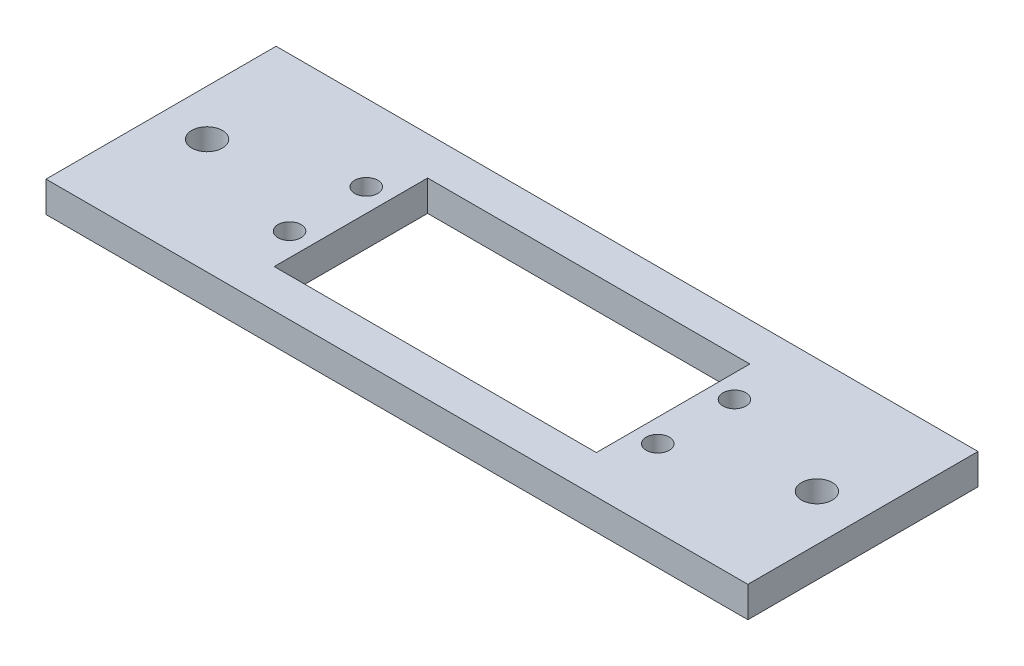
SolidWorks part; units mm, degrees
material "Balsa"
ref_plane "Front Plane" through (0, 0, 0) normal (0, 0, 1) x (1, 0, 0)
ref_plane "Top Plane" through (0, 0, 0) normal (0, 1, 0) x (1, 0, 0)
ref_plane "Right Plane" through (0, 0, 0) normal (1, 0, 0) x (0, 0, -1)
sketch "Sketch1" plane through (0, 0, 0) normal (0, 1, 0) x (1, 0, 0)
  line L0 (-21, 10) -> (-27.75, 10) construction
  line L1 (-21, -10) -> (21, -10)
  line L2 (-21, -10) -> (-21, 10)
  line L3 (-21, 10) -> (21, 10)
  line L4 (21, -10) -> (21, 10)
  line L5 (-21, -10) -> (21, 10) construction
  line L6 (-21, 10) -> (21, -10) construction
  line L7 (-27.75, 10) -> (-27.75, -10) construction
  line L8 (-27.75, -10) -> (-21, -10) construction
  line L9 (0, 10) -> (0, -10) construction
  line L10 (27.75, -10) -> (21, -10) construction
  line L11 (27.75, 10) -> (27.75, -10) construction
  line L12 (21, 10) -> (27.75, 10) construction
  line L13 (-53.9162, 0) -> (53.9162, 0) construction
  line L14 (0, 15) -> (0, -15) construction
  line L15 (-45.75, 15) -> (45.75, 15)
  line L16 (-45.75, 15) -> (-45.75, -15)
  line L17 (-45.75, -15) -> (45.75, -15)
  line L18 (45.75, 15) -> (45.75, -15)
  line L19 (-45.75, 0) -> (45.75, 0) construction
  circle A0 centre (-39.75, 0) radius 2
  circle A1 centre (39.75, 0) radius 2
  point P0 (0, 0)
  point P14 (0, 0)
  point P27 (0, 0)
  dimension "D4" = 4
  dimension "D1" = 20
  dimension "D2" = 42
  dimension "D3" = 55.5
  dimension "D5" = 30
  dimension "D6" = 12
  dimension "D7" = 6
extrude "Boss-Extrude1" add sketch "Sketch1" along normal blind 4
sketch "Sketch2" plane through (0, 4, 0) normal (0, 1, 0) x (1, 0, 0)
  line L0 (0, 15) -> (0, -15) construction
  line L1 (45.75, 15) -> (-45.75, 15) construction
  line L2 (-45.75, -15) -> (45.75, -15) construction
  line L3 (-45.75, 0) -> (45.75, 0) construction
  line L4 (-45.75, 15) -> (-45.75, -15) construction
  line L5 (45.75, -15) -> (45.75, 15) construction
  line L6 (-24, 15) -> (-24, -15) construction
  line L7 (24, 15) -> (24, -15) construction
  circle A0 centre (-24, 5) radius 1.5
  circle A1 centre (-24, -5) radius 1.5
  circle A2 centre (24, -5) radius 1.5
  circle A3 centre (24, 5) radius 1.5
  dimension "D1" = 3
  dimension "D3" = 48
  dimension "D2" = 10
extrude "Cut-Extrude1" cut sketch "Sketch2" against normal through all
